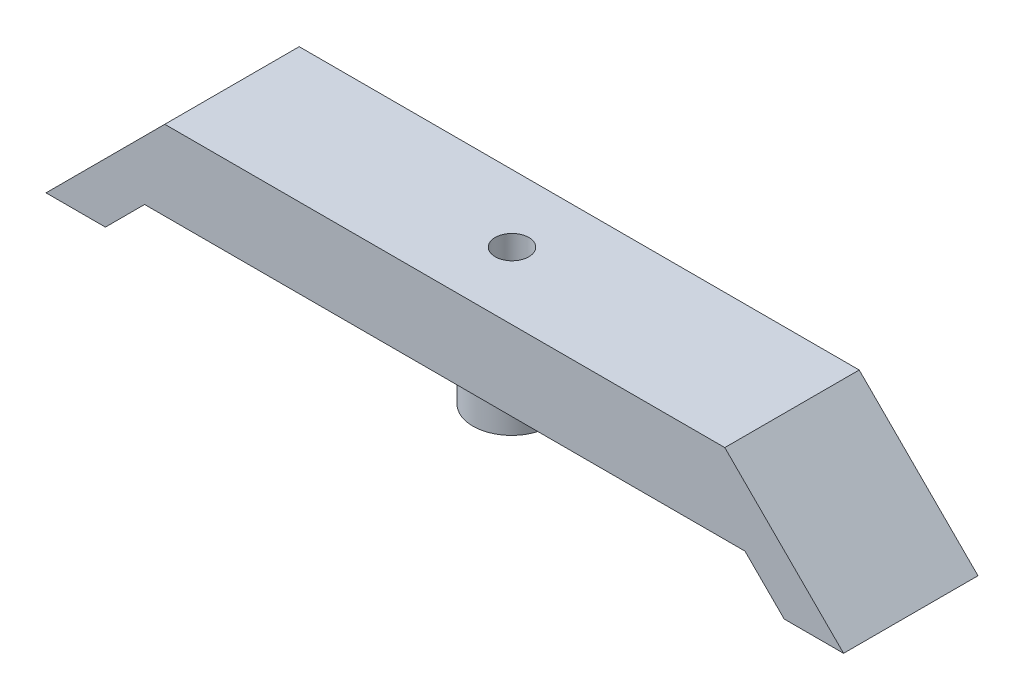
SolidWorks part; units mm, degrees
ref_plane "Ön Düzlem" through (0, 0, 0) normal (0, 0, 1) x (1, 0, 0)
ref_plane "Üst Düzlem" through (0, 0, 0) normal (0, 1, 0) x (1, 0, 0)
ref_plane "Sağ Düzlem" through (0, 0, 0) normal (1, 0, 0) x (0, 0, -1)
sketch "Çizim1" plane through (0, 0, 0) normal (0, 0, 1) x (1, 0, 0)
  line L0 (0, 0) -> (-50, 0)
  line L1 (-50, 0) -> (-60.6066, -10.6066)
  line L2 (0, 0) -> (10.6066, -10.6066)
  line L4 (-60.6066, -10.6066) -> (-55.3033, -10.6066)
  line L5 (-55.3033, -10.6066) -> (-51.8024, -7.1057)
  line L6 (-51.8024, -7.1057) -> (1.8024, -7.1057)
  line L7 (5.3033, -10.6066) -> (1.8024, -7.1057)
  line L8 (10.6066, -10.6066) -> (5.3033, -10.6066)
  point P11 (-25, -7.1057)
extrude "Yükseklik-Ekstrüzyon1" add sketch "Çizim1" along normal blind 12
sketch "Çizim2" plane through (0, -7.1057, 0) normal (0, -1, 0) x (1, 0, 0)
  line L0 (-51.8024, 12) -> (1.8024, 12)
  line L1 (1.8024, 12) -> (1.8024, 0)
  line L2 (1.8024, 0) -> (-51.8024, 0)
  line L3 (-51.8024, 0) -> (-51.8024, 12)
  line L4 (1.8024, 12) -> (1.8024, 0)
  line L5 (1.8024, 12) -> (-51.8024, 0)
  line L6 (-51.8024, 12) -> (1.8024, 0)
  circle A0 centre (-25, 6) radius 1.5
extrude "Kes-Ekstrüzyon1" cut sketch "Çizim2" against normal blind 12 contours L5 A0 L6 | L5 A0 L6 | L6 A0 L5 | L6 A0 L5
sketch "Çizim3" plane through (0, -7.1057, 0) normal (0, -1, 0) x (1, 0, 0)
  arc A1 (-23.6302, 5.3453) -> (-23.5722, 5.4754) centre (-25.0009, 6.034) ccw
  arc A4 (-23.6302, 5.3453) -> (-23.5722, 5.4754) centre (-25.0009, 6.034) ccw
  circle A5 centre (-25.0009, 6.034) radius 3.452
  circle A6 centre (-25.0009, 6.034) radius 1.534
extrude "Yükseklik-Ekstrüzyon2" add sketch "Çizim3" along normal blind 5 contours A5 A6 A1
sketch "Çizim4" plane through (0, 0, 0) normal (0, 1, 0) x (1, 0, 0)
  circle A0 centre (-25, -6) radius 3.5
  circle A1 centre (-25, -6) radius 1.5
